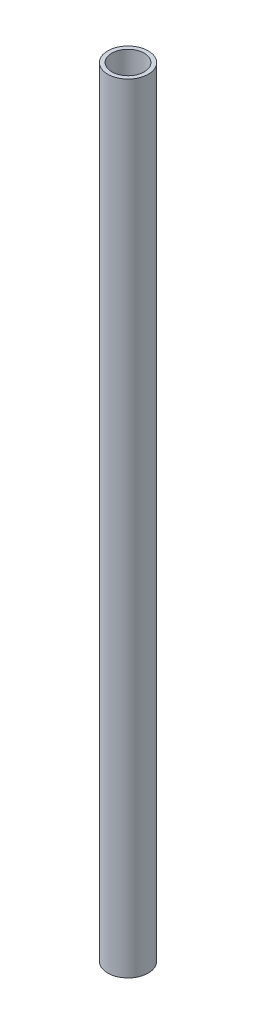
SolidWorks part; units mm, degrees
ref_plane "Front Plane" through (0, 0, 0) normal (0, 0, 1) x (1, 0, 0)
ref_plane "Top Plane" through (0, 0, 0) normal (0, 1, 0) x (1, 0, 0)
ref_plane "Right Plane" through (0, 0, 0) normal (1, 0, 0) x (0, 0, -1)
sketch "Sketch1" plane through (0, 0, 0) normal (0, 1, 0) x (1, 0, 0)
  circle A0 centre (0, -0.5062) radius 15.875
  circle A1 centre (0, -0.5062) radius 12.7
  dimension "D1" = 31.75
  dimension "D2" = 3.175
extrude "Boss-Extrude1" add sketch "Sketch1" along normal blind 609.6
